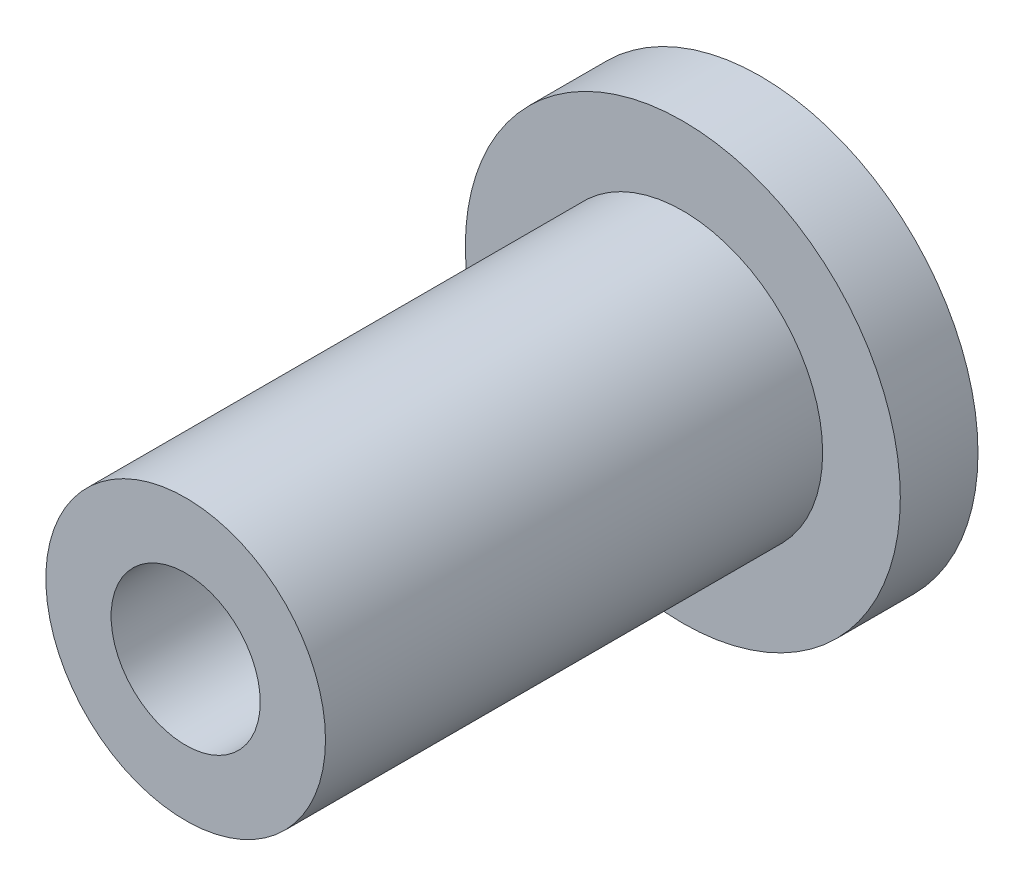
SolidWorks part; units mm, degrees
ref_plane "前视基准面" through (0, 0, 0) normal (0, 0, 1) x (1, 0, 0)
ref_plane "上视基准面" through (0, 0, 0) normal (0, 1, 0) x (1, 0, 0)
ref_plane "右视基准面" through (0, 0, 0) normal (1, 0, 0) x (0, 0, -1)
other "Configuration Table"
sketch "Sketch1" plane through (0, 0, 0) normal (0, 0, 1) x (1, 0, 0)
  circle A0 centre (0, 0) radius 7
  dimension "D1" = 14
extrude "Boss-Extrude1" add sketch "Sketch1" along normal blind 2.5
sketch "Sketch2" plane through (0, 0, 2.5) normal (0, 0, 1) x (1, 0, 0)
  circle A0 centre (0, 0) radius 4.5
  dimension "D1" = 9
extrude "Boss-Extrude2" add sketch "Sketch2" along normal blind 16
sketch "Sketch3" plane through (0, 0, 18.5) normal (0, 0, 1) x (1, 0, 0)
  circle A5 centre (0, 0) radius 2.4
  dimension "D1" = 4.8
extrude "Cut-Extrude1" cut sketch "Sketch3" against normal blind 5
